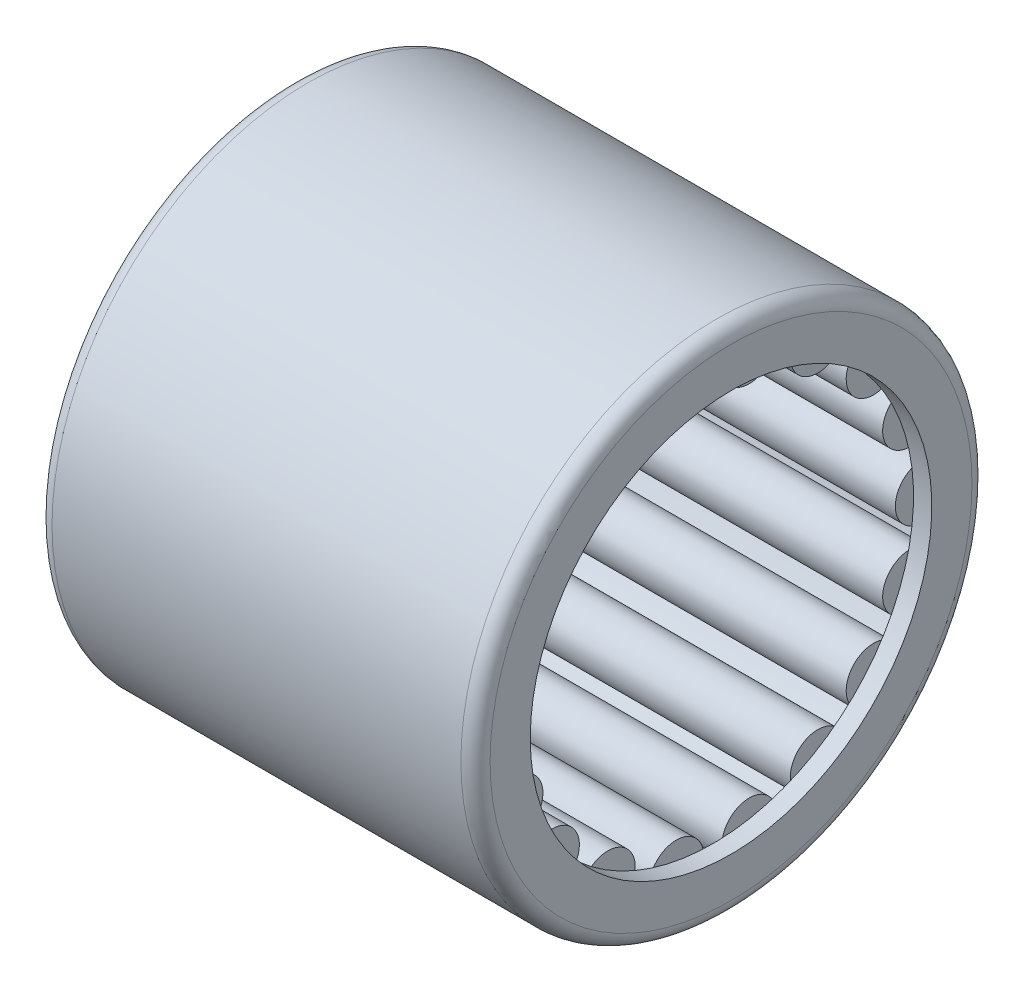
SolidWorks part; units mm, degrees
ref_plane "前视基准面" through (0, 0, 0) normal (0, 0, 1) x (1, 0, 0)
ref_plane "上视基准面" through (0, 0, 0) normal (0, 1, 0) x (1, 0, 0)
ref_plane "右视基准面" through (0, 0, 0) normal (1, 0, 0) x (0, 0, -1)
other "Configuration Table"
sketch "草图2" plane through (0, 0, 0) normal (0, 0, 1) x (1, 0, 0)
sketch "草图3" plane through (0, 0, 0) normal (0, 0, 1) x (1, 0, 0)
  line L0 (-6, 7) -> (-6, 5.5)
  line L1 (-6, 5.5) -> (-5.5, 5.5)
  line L2 (-5.5, 5.5) -> (-5.5, 6.5)
  line L3 (-5.5, 6.5) -> (5.5, 6.5)
  line L4 (5.5, 6.5) -> (5.5, 5.5)
  line L5 (5.5, 5.5) -> (6, 5.5)
  line L6 (6, 5.5) -> (6, 7)
  line L7 (6, 7) -> (-6, 7)
  line L8 (55, 0) -> (-55, 0) construction
  line L10 (0, -55) -> (0, 55) construction
  line L11 (-6.2027, 0) -> (6.3474, 0) construction
  point P10 (-5.5, 6)
  dimension "D1" = 5.5
  dimension "D2" = 5.5
  dimension "D3" = 0.5
  dimension "D4" = 7
  dimension "D5" = 0.5
  dimension "D6" = 0.5
  dimension "D7" = 6
  dimension "D8" = 6
revolve "旋转1" add sketch "草图3" angle 360 about L11
sketch "草图5" plane through (5.5, 0, 0) normal (-1, 0, 0) x (0, 0, 1)
  line L0 (6.6, 0) -> (-6.6, 0) construction
  circle A0 centre (-5.75, 0) radius 0.75
  circle A1 centre (0, 0) radius 6.5 construction
  point P4 (-3.8285, 0)
  point P5 (-4.7617, 0)
  point P6 (-5.2936, 0)
  dimension "D1" = 1.5
extrude "凸台-拉伸3" add sketch "草图5" along normal up to surface (11 mm away) separate body contours A0 up to face at (-5.5, 0, 6.5)
pattern_circular "阵列(圆周)8" count 18 over 360 about axis through (0, 0, 0) along (1, 0, 0) of bodies 107
fillet "圆角1" radius 0.4 4 edges at (5.5, 0, 6.5) (-5.5, 0, 6.5) (6, 0, 7) (-6, 0, 7)
